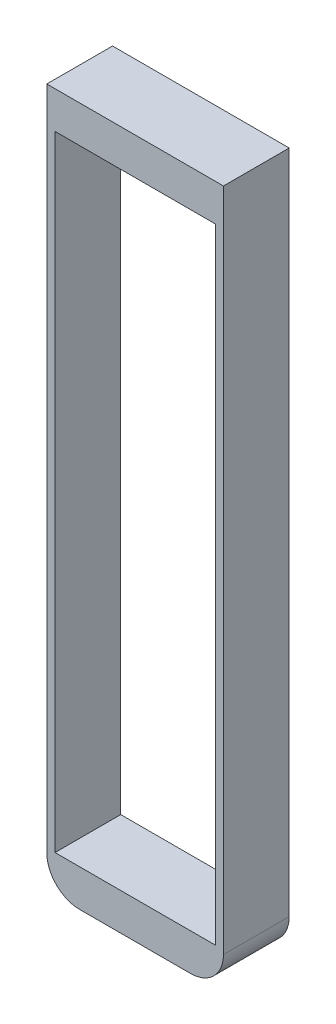
SolidWorks part; units mm, degrees
ref_plane "Спереди" through (0, 0, 0) normal (0, 0, 1) x (1, 0, 0)
ref_plane "Сверху" through (0, 0, 0) normal (0, 1, 0) x (1, 0, 0)
ref_plane "Справа" through (0, 0, 0) normal (1, 0, 0) x (0, 0, -1)
sketch "Эскиз1" plane through (0, 0, 0) normal (0, 0, 1) x (1, 0, 0)
  line L1 (0, 0) -> (43, 0)
  line L2 (0, 0) -> (0, 170)
  line L3 (0, 170) -> (43, 170)
  line L4 (43, 0) -> (43, 170)
  dimension "D1" = 43
  dimension "D2" = 170
extrude "Бобышка-Вытянуть1" add sketch "Эскиз1" along normal blind 16
sketch "Эскиз3" plane through (0, 0, 16) normal (0, 0, 1) x (1, 0, 0)
  line L0 (21.5, 0) -> (21.5, 170) construction
  line L1 (0, 0) -> (43, 0) construction
  line L2 (43, 170) -> (0, 170) construction
  line L4 (2, 161) -> (41, 161)
  line L5 (2, 161) -> (2, 9)
  line L6 (2, 9) -> (41, 9)
  line L7 (41, 161) -> (41, 9)
  line L8 (2, 161) -> (41, 9) construction
  line L9 (2, 9) -> (41, 161) construction
  point P6 (21.5, 85)
  dimension "D1" = 39
  dimension "D2" = 152
extrude "Вырез-Вытянуть1" cut sketch "Эскиз3" against normal through all
fillet "Скругление3" radius 8 2 edges at (43, 0, 8) (0, 0, 8)
